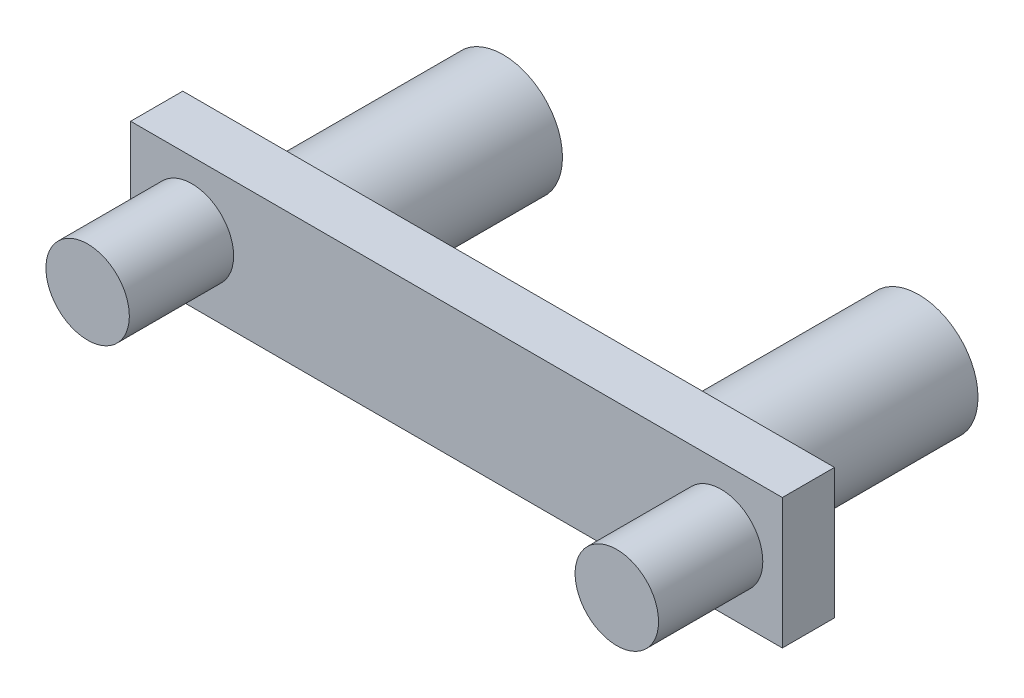
SolidWorks part; units mm, degrees
ref_plane "Front Plane" through (0, 0, 0) normal (0, 0, 1) x (1, 0, 0)
ref_plane "Top Plane" through (0, 0, 0) normal (0, 1, 0) x (1, 0, 0)
ref_plane "Right Plane" through (0, 0, 0) normal (1, 0, 0) x (0, 0, -1)
sketch "Sketch1" plane through (0, 0, 0) normal (0, 0, 1) x (1, 0, 0)
  line L0 (0, 0) -> (25, 0)
  line L1 (25, 0) -> (25, 5)
  line L2 (25, 5) -> (0, 5)
  line L3 (0, 5) -> (0, 0)
  dimension "D1" = 25
  dimension "D2" = 5
extrude "Boss-Extrude1" add sketch "Sketch1" along normal blind 2
sketch "Sketch2" plane through (0, 0, 2) normal (0, 0, 1) x (1, 0, 0)
  line L0 (0, 5) -> (0, 0) construction
  line L1 (25, 0) -> (25, 5) construction
  line L2 (0, 0) -> (25, 0) construction
  circle A0 centre (2.35, 2.5) radius 1.6
  circle A1 centre (22.65, 2.5) radius 1.6
  dimension "D1" = 3.2
  dimension "D2" = 3.2
  dimension "D3" = 2.35
  dimension "D4" = 2.35
  dimension "D5" = 2.5
  dimension "D6" = 2.5
extrude "Boss-Extrude2" add sketch "Sketch2" along normal blind 4
sketch "Sketch3" plane through (0, 0, 0) normal (0, 0, -1) x (-1, 0, 0)
  line L0 (-25, 0) -> (-25, 5) construction
  circle A0 centre (-20.47, 2.323) radius 2.275
  circle A1 centre (-4.53, 2.323) radius 2.275
  circle A2 centre (-20.47, 2.323) radius 1.6
  circle A3 centre (-4.53, 2.323) radius 1.6
  dimension "D1" = 4.55
  dimension "D2" = 4.55
  dimension "D3" = 3.2
  dimension "D4" = 3.2
  dimension "D6" = 4.53
  dimension "D5" = 15.94
extrude "Boss-Extrude3" add sketch "Sketch3" along normal blind 7.76
